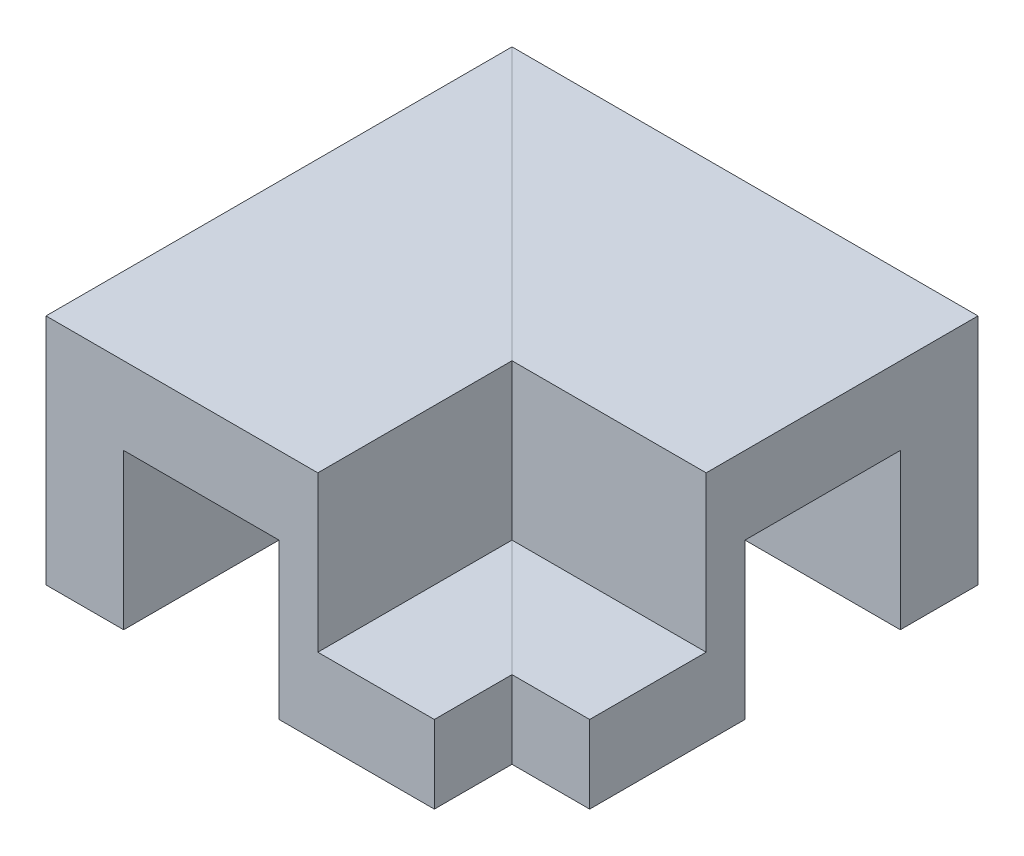
SolidWorks part; units mm, degrees
material "ABS"
ref_plane "Front Plane" through (0, 0, 0) normal (0, 0, 1) x (1, 0, 0)
ref_plane "Top Plane" through (0, 0, 0) normal (0, 1, 0) x (1, 0, 0)
ref_plane "Right Plane" through (0, 0, 0) normal (1, 0, 0) x (0, 0, -1)
sketch "Sketch2" plane through (0, 0, 0) normal (0, 1, 0) x (1, 0, 0)
  line L2 (19.05, 0) -> (0, 0)
  line L3 (0, 0) -> (0, -19.05)
  dimension "D4" = 19.05
ref_plane "Plane1" through (0, 0, 19.05) normal (0, 0, 1) x (1, 0, 0)
sketch "Sketch3" plane through (0, 0, 19.05) normal (0, 0, 1) x (1, 0, 0)
  line L0 (0, 0) -> (12.7, 0)
  line L1 (12.7, 0) -> (12.7, 6.35)
  line L2 (12.7, 6.35) -> (3.175, 6.35)
  line L3 (3.175, 6.35) -> (3.175, 19.05)
  line L4 (3.175, 19.05) -> (-19.05, 19.05)
  line L5 (-19.05, 19.05) -> (-19.05, 0)
  line L6 (-19.05, 0) -> (-12.7, 0)
  line L7 (-12.7, 0) -> (-12.7, 12.7)
  line L8 (-12.7, 12.7) -> (0, 12.7)
  line L9 (0, 12.7) -> (0, 0)
  dimension "D1" = 12.7
  dimension "D2" = 12.7
  dimension "D3" = 12.7
  dimension "D4" = 9.525
  dimension "D5" = 6.35
  dimension "D6" = 6.35
  dimension "D7" = 6.35
sweep "Sweep1" add profiles "Sketch3" path "Sketch2"
